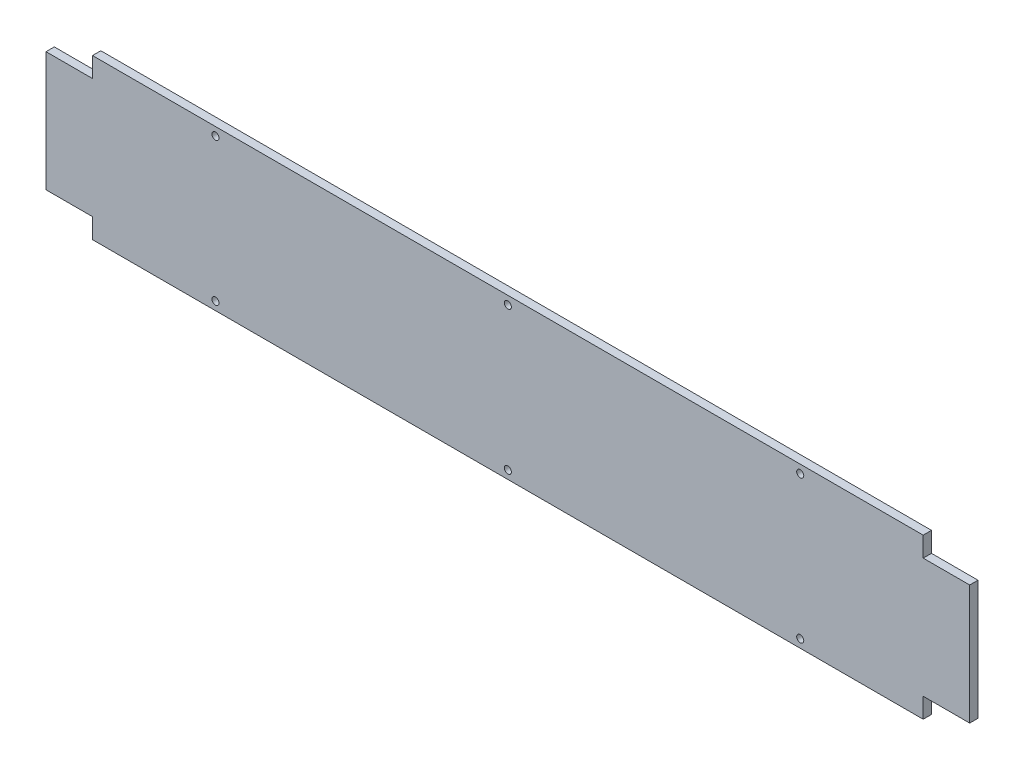
SolidWorks part; units mm, degrees
ref_plane "Front Plane" through (0, 0, 0) normal (0, 0, 1) x (1, 0, 0)
ref_plane "Top Plane" through (0, 0, 0) normal (0, 1, 0) x (1, 0, 0)
ref_plane "Right Plane" through (0, 0, 0) normal (1, 0, 0) x (0, 0, -1)
sketch "Sketch1" plane through (0, 0, 0) normal (0, 0, 1) x (1, 0, 0)
  line L9 (0, 0) -> (500, 0)
  line L10 (0, 0) -> (0, 96)
  line L11 (0, 96) -> (500, 96)
  line L12 (500, 0) -> (500, 96)
  dimension "D1" = 96
  dimension "D2" = 500
extrude "Boss-Extrude1" add sketch "Sketch1" along normal blind 5
sketch "Sketch2" plane through (0, 0, 5) normal (0, 0, 1) x (1, 0, 0)
  line L0 (0, 96) -> (0, 0) construction
  line L3 (500, 96) -> (0, 96) construction
  line L4 (32.0519, 48) -> (507.2554, 48) construction
  circle A0 centre (74, 91) radius 2.125
  circle A1 centre (250, 91) radius 2.125
  circle A2 centre (426, 91) radius 2.125
  circle A3 centre (426, 5) radius 2.125
  circle A4 centre (250, 5) radius 2.125
  circle A5 centre (74, 5) radius 2.125
  dimension "D1" = 4.25
  dimension "D2" = 4.25
  dimension "D3" = 4.25
  dimension "D6" = 176
  dimension "D4" = 74
  dimension "D5" = 176
  dimension "D7" = 5
  dimension "D8" = 48
extrude "Cut-Extrude1" cut sketch "Sketch2" against normal blind 5
sketch "Sketch3" plane through (0, 0, 5) normal (0, 0, 1) x (1, 0, 0)
  line L0 (500, 0) -> (500, 96) construction
  line L1 (500, 84) -> (528, 84)
  line L2 (500, 84) -> (500, 12)
  line L3 (500, 12) -> (528, 12)
  line L4 (528, 84) -> (528, 12)
  line L5 (0, 96) -> (0, 0) construction
  line L6 (0, 84) -> (-28, 84)
  line L7 (0, 84) -> (0, 12)
  line L8 (0, 12) -> (-28, 12)
  line L9 (-28, 84) -> (-28, 12)
  line L10 (500, 96) -> (0, 96) construction
  line L11 (0, 0) -> (500, 0) construction
  dimension "D1" = 12
  dimension "D2" = 28
  dimension "D3" = 12
  dimension "D4" = 12
  dimension "D5" = 12
  dimension "D6" = 28
extrude "Boss-Extrude2" add sketch "Sketch3" against normal blind 5
